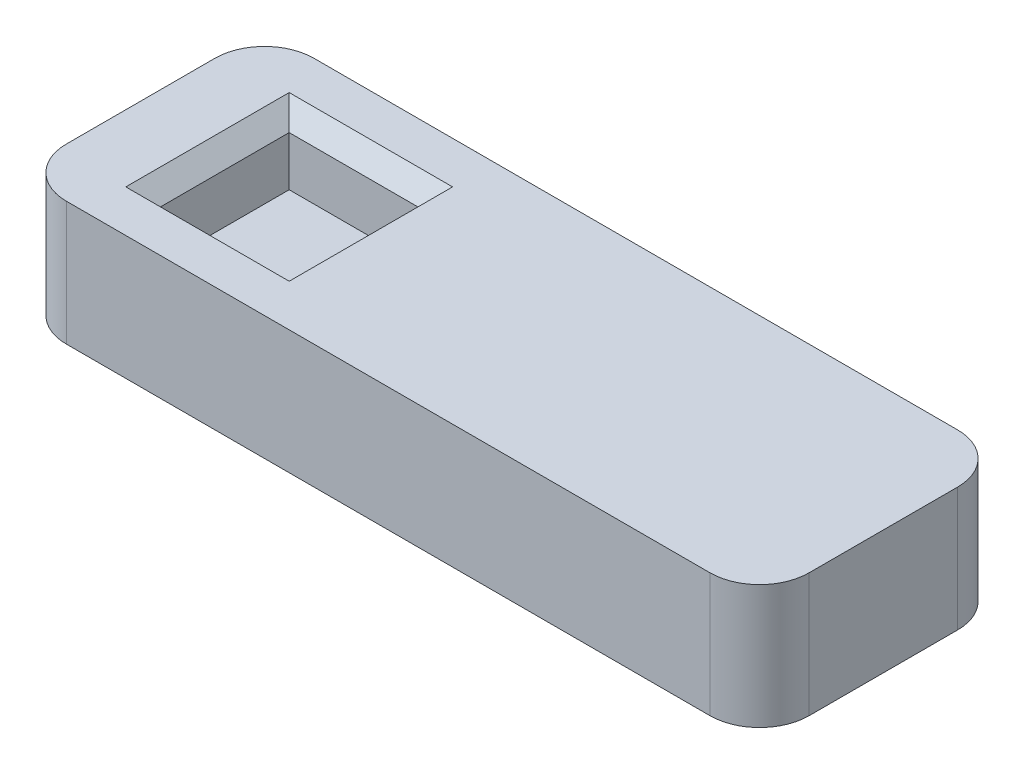
SolidWorks part; units mm, degrees
ref_plane "Plano frontal" through (0, 0, 0) normal (0, 0, 1) x (1, 0, 0)
ref_plane "Plano superior" through (0, 0, 0) normal (0, 1, 0) x (1, 0, 0)
ref_plane "Plano direito" through (0, 0, 0) normal (1, 0, 0) x (0, 0, -1)
sketch "Esboço1" plane through (0, 0, 0) normal (0, 1, 0) x (1, 0, 0)
  line L1 (0, 0) -> (30, 0)
  line L2 (0, 0) -> (0, 10)
  line L3 (0, 10) -> (30, 10)
  line L4 (30, 0) -> (30, 10)
  dimension "D1" = 10
  dimension "D2" = 30
extrude "Ressalto-extrusão1" add sketch "Esboço1" along normal blind 5
sketch "Esboço2" plane through (0, 5, 0) normal (0, 1, 0) x (1, 0, 0)
  line L0 (-2.1523, 5) -> (33.7028, 5) construction
  line L2 (3.4, 7.6) -> (8.6, 7.6)
  line L3 (3.4, 7.6) -> (3.4, 2.4)
  line L4 (3.4, 2.4) -> (8.6, 2.4)
  line L5 (8.6, 7.6) -> (8.6, 2.4)
  line L6 (3.4, 7.6) -> (8.6, 2.4) construction
  line L7 (3.4, 2.4) -> (8.6, 7.6) construction
  point P2 (6, 5)
  dimension "D1" = 5
  dimension "D2" = 5.2
  dimension "D3" = 5.2
  dimension "D4" = 6
extrude "Corte-extrusão1" cut sketch "Esboço2" against normal blind 2.7
chamfer "Chanfro1" distance 0.7 angle 45 4 edges at (6, 5, -2.4) (8.6, 5, -5) (3.4, 5, -5) (6, 5, -7.6)
fillet "Filete1" radius 2 1 edges at (30, 2.5, 0)
fillet "Filete2" radius 2 1 edges at (30, 2.5, -10)
fillet "Filete3" radius 2 1 edges at (0, 2.5, 0)
fillet "Filete4" radius 2 1 edges at (0, 2.5, -10)
